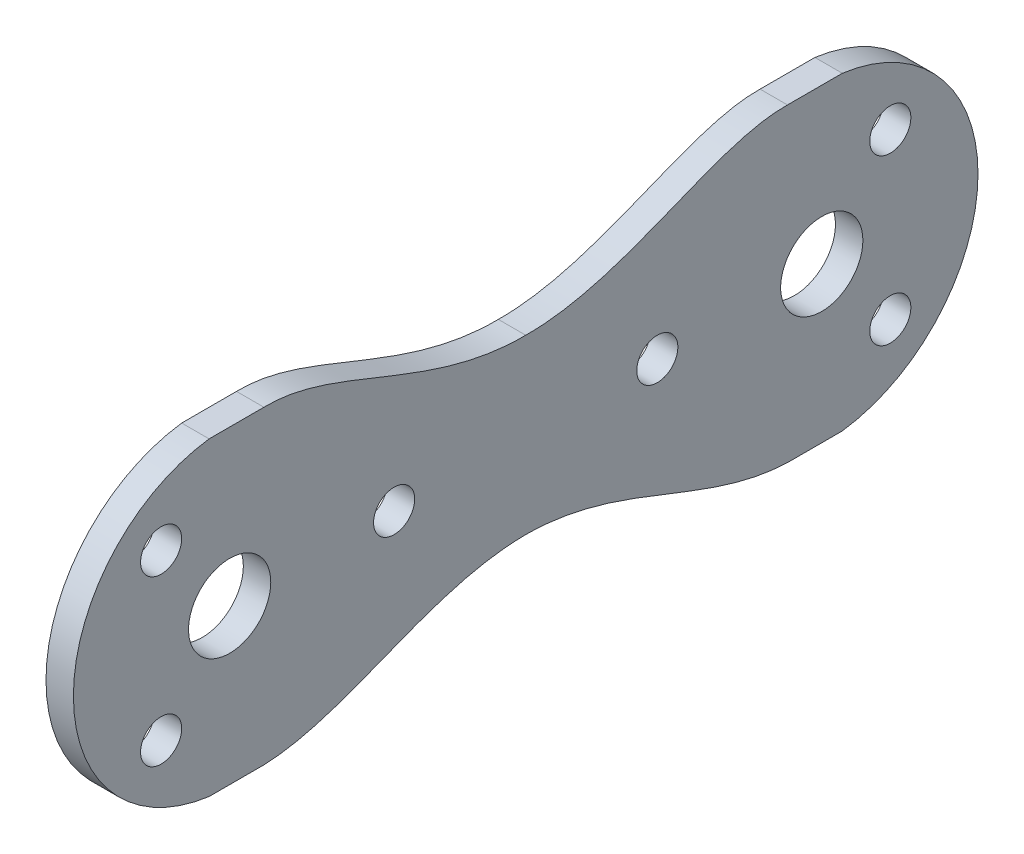
SolidWorks part; units mm, degrees
ref_plane "Piano frontale" through (0, 0, 0) normal (0, 0, 1) x (1, 0, 0)
ref_plane "Piano superiore" through (0, 0, 0) normal (0, 1, 0) x (1, 0, 0)
ref_plane "Piano destro" through (0, 0, 0) normal (1, 0, 0) x (0, 0, -1)
sketch "Schizzo1" plane through (0, 0, 0) normal (1, 0, 0) x (0, 0, -1)
  line L4 (-2.501, -10.3) -> (-2.501, -11.3)
  line L5 (-2.501, -11.3) -> (1.499, -11.3)
  line L7 (1.499, 11.3) -> (-2.501, 11.3)
  line L8 (-2.501, 11.3) -> (-2.501, 10.3)
  line L15 (-43.202, 0) -> (0, 0)
  line L30 (-2.501, 10.3) -> (-7.501, 10.3)
  line L31 (-7.501, 10.3) -> (-7.501, 6.3)
  line L32 (-7.501, 6.3) -> (-35.701, 6.3)
  line L35 (-21.601, 6.3) -> (-21.601, -6.3)
  line L36 (-35.701, -6.3) -> (-7.501, -6.3)
  line L37 (-7.501, -6.3) -> (-7.501, -10.3)
  line L38 (-7.501, -10.3) -> (-2.501, -10.3)
  line L40 (-35.701, -10.3) -> (-40.701, -10.3)
  line L41 (-35.701, -6.3) -> (-35.701, -10.3)
  line L42 (-35.701, 10.3) -> (-35.701, 6.3)
  line L43 (-40.701, 10.3) -> (-35.701, 10.3)
  line L47 (-40.701, 11.3) -> (-40.701, 10.3)
  line L48 (-44.701, 11.3) -> (-40.701, 11.3)
  line L49 (-40.701, -11.3) -> (-44.701, -11.3)
  line L50 (-40.701, -10.3) -> (-40.701, -11.3)
  arc A11 (-44.701, 11.3) -> (-44.701, -11.3) centre (-43.202, 0) ccw
  arc A14 (1.499, 11.3) -> (1.499, -11.3) centre (0, 0) cw
  circle A16 centre (-48.202, 6) radius 1.5
  circle A17 centre (-48.202, -6) radius 1.5
  circle A18 centre (-31.202, 0) radius 1.5
  circle A19 centre (-12, 0) radius 1.5
  circle A20 centre (5, 6) radius 1.5
  circle A21 centre (5, -6) radius 1.5
  circle A22 centre (-43.202, 0) radius 3
  circle A23 centre (0, 0) radius 3
  spline S0 degree 3 poles (-2.501, 11.3) (-7.8399, 11.4296) (-14.3518, 6.2167) (-21.601, 6.3) knots 0 0 0 0 1 1 1 1
  spline S1 degree 3 poles (-2.501, -11.3) (-8.7462, -11.0636) (-14.4327, -6.3399) (-21.601, -6.3) knots 0 0 0 0 1 1 1 1
  spline S2 degree 3 poles (-40.701, -11.3) (-34.4558, -11.0636) (-28.7694, -6.3399) (-21.601, -6.3) knots 0 0 0 0 1 1 1 1
  spline S3 degree 3 poles (-40.701, 11.3) (-35.3621, 11.4296) (-28.8502, 6.2167) (-21.601, 6.3) knots 0 0 0 0 1 1 1 1
  point P17 (11.399, 0)
  point P41 (-21.601, 0)
  dimension "D7" = 11.399
  dimension "D12" = 6
  dimension "D14" = 3
  dimension "D15" = 3
  dimension "D16" = 3
  dimension "D17" = 3
  dimension "D18" = 3
  dimension "D19" = 3
  dimension "D8" = 6
  dimension "D1" = 33
  dimension "D2" = 22.6
  dimension "D3" = 11.3
  dimension "D4" = 1
  dimension "D5" = 1
  dimension "D6" = 4
  dimension "D9" = 5
  dimension "D10" = 4
  dimension "D11" = 4
  dimension "D20" = 5
  dimension "D21" = 12
  dimension "D22" = 6
  dimension "D23" = 12
  dimension "D24" = 12
  dimension "D25" = 5
extrude "Estrusione-Estrusione1" add sketch "Schizzo1" along normal blind 2
